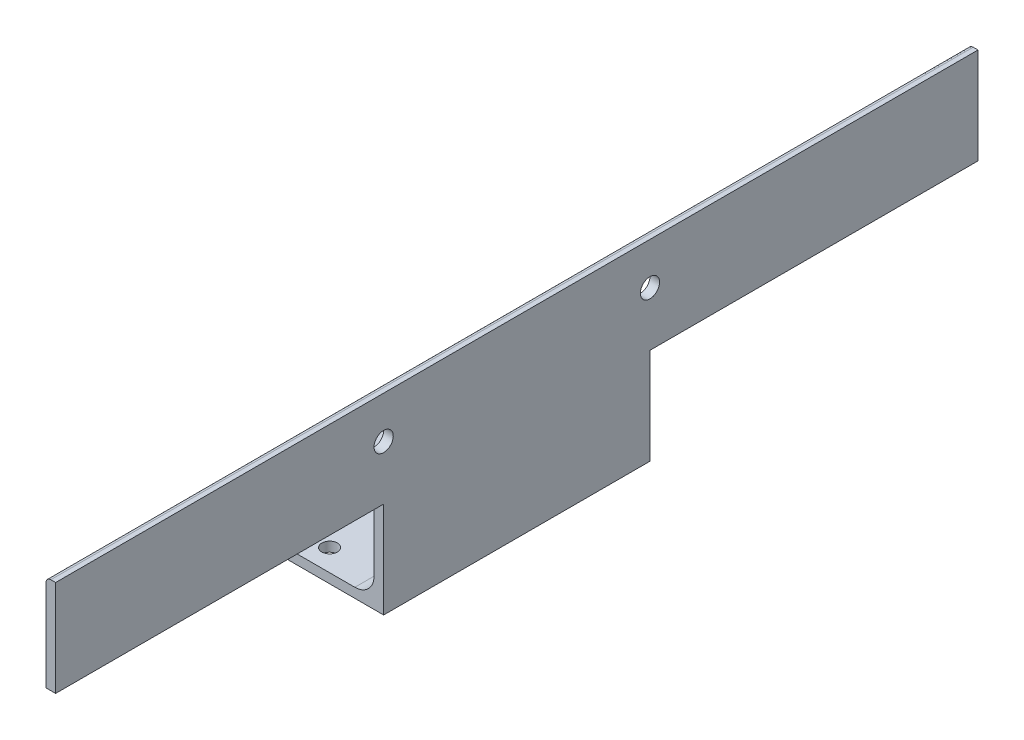
SolidWorks part; units mm, degrees
ref_plane "Front Plane" through (0, 0, 0) normal (0, 0, 1) x (1, 0, 0)
ref_plane "Top Plane" through (0, 0, 0) normal (0, 1, 0) x (1, 0, 0)
ref_plane "Right Plane" through (0, 0, 0) normal (1, 0, 0) x (0, 0, -1)
sketch "Sketch0" plane through (0, 0, 0) normal (0, 0, 1) x (1, 0, 0)
  line L0 (-31.75, -31.75) -> (31.75, -31.75)
  line L1 (31.75, -31.75) -> (31.75, 31.75)
  line L2 (31.75, 0) -> (0, 0) construction
  line L3 (0, 0) -> (0, -31.75) construction
  line L4 (28.575, -22.225) -> (28.575, 31.75) construction
  line L5 (22.225, -28.575) -> (-31.75, -28.575) construction
  arc A0 (28.575, -22.225) -> (22.225, -28.575) centre (22.225, -22.225) cw
  point P3 (26.7151, -26.7151)
  dimension "Inside Corner Radius" = 6.35
  dimension "Outside Height" = 63.5
  dimension "Inside Height" = 60.325
  dimension "Inside Width" = 60.325
  dimension "Wall Thickness" = 3.175
  dimension "D1" = 3.175
  dimension "Outside Width" = 63.5
sketch "Sketch1" plane through (0, 0, 0) normal (1, 0, 0) x (0, 0, -1)
  line L0 (152.4, 0) -> (-152.4, 0)
  point P4 (0, 0)
  dimension "Length" = 304.8
sketch "Sketch2" plane through (0, 0, 0) normal (0, 0, 1) x (1, 0, 0)
  line L0 (-31.75, -31.75) -> (31.75, -31.75)
  line L1 (31.75, -31.75) -> (31.75, 31.75)
  line L2 (31.75, 31.75) -> (28.575, 31.75) construction
  line L3 (28.575, 30.1625) -> (28.575, -22.225)
  line L4 (22.225, -28.575) -> (-30.1625, -28.575)
  line L5 (-31.75, -31.75) -> (-31.75, -28.575) construction
  line L6 (30.1625, 31.75) -> (31.75, 31.75)
  line L7 (-31.75, -30.1625) -> (-31.75, -31.75)
  line L8 (31.75, 0) -> (0, 0) construction
  line L9 (0, 0) -> (0, -31.75) construction
  arc A0 (28.575, 30.1625) -> (30.1625, 31.75) centre (30.1625, 30.1625) cw
  arc A1 (-31.75, -30.1625) -> (-30.1625, -28.575) centre (-30.1625, -30.1625) cw
  arc A2 (28.575, -22.225) -> (22.225, -28.575) centre (22.225, -22.225) cw
  dimension "Inside Radius" = 6.35
  dimension "Height" = 63.5
  dimension "Width" = 63.5
  dimension "Thickness" = 3.175
extrude "Boss-Extrude1" add sketch "Sketch2" along normal mid plane 304.8
sketch "Break Locations" plane through (0, 0, 0) normal (1, 0, 0) x (0, 0, -1)
  line L0 (-87.63, 0) -> (87.63, 0)
  line L1 (-152.4, -31.75) -> (-152.4, 31.75) construction
  line L2 (152.4, -31.75) -> (152.4, 31.75) construction
  point P0 (-98.425, 0)
  point P1 (98.425, 0)
  point P10 (0, 0)
  point P11 (87.63, 0)
  point P13 (-87.63, 0)
  dimension "D1" = 53.975
  dimension "D2" = 53.975
  dimension "D3" = 64.77
sketch "Sketch3" plane through (0, -28.575, 0) normal (0, 1, 0) x (1, 0, 0)
  line L0 (-3.9687, 152.4) -> (-3.9687, -152.4) construction
  line L1 (22.225, 152.4) -> (-30.1625, 152.4) construction
  line L2 (22.225, -152.4) -> (-30.1625, -152.4) construction
  line L3 (-27.3219, 0) -> (19.3844, 0) construction
  circle A0 centre (-14.3219, 8.79) radius 2.585
  circle A1 centre (6.6781, 8.79) radius 2.585
  circle A2 centre (-14.3219, 36.79) radius 2.585
  circle A3 centre (6.6781, 36.79) radius 2.585
  circle A4 centre (-14.3219, -36.79) radius 2.585
  circle A5 centre (6.6781, -36.79) radius 2.585
  circle A6 centre (6.6781, -8.79) radius 2.585
  circle A7 centre (-14.3219, -8.79) radius 2.585
  point P24 (-3.9688, 0)
  point P25 (-3.9687, 0)
  dimension "D1" = 5.17
  dimension "D2" = 5.17
  dimension "D3" = 28
  dimension "D4" = 8.79
  dimension "D5" = 8.79
  dimension "D6" = 28
extrude "Cut-Extrude1" cut sketch "Sketch3" against normal through all
sketch "Sketch4" plane through (31.75, 0, 0) normal (1, 0, 0) x (0, 0, -1)
  line L6 (-152.4, 0) -> (-44, 0)
  line L7 (-152.4, -31.75) -> (-152.4, 31.75) construction
  line L8 (-44, 0) -> (-44, -48.0447)
  line L9 (-44, -48.0447) -> (-168.6254, -48.0447)
  line L10 (-168.6254, -48.0447) -> (-168.6254, 0)
  line L11 (-168.6254, 0) -> (-152.4, 0)
  line L12 (0, 0) -> (0, -31.75) construction
  line L13 (-152.4, -31.75) -> (152.4, -31.75) construction
  line L14 (168.6254, -48.0447) -> (168.6254, 0)
  line L15 (44, -48.0447) -> (168.6254, -48.0447)
  line L16 (44, 0) -> (44, -48.0447)
  line L17 (152.4, 0) -> (44, 0)
  line L18 (168.6254, 0) -> (152.4, 0)
  dimension "D1" = 88
extrude "Cut-Extrude2" cut sketch "Sketch4" against normal through all
sketch "Sketch5" plane through (31.75, 0, 0) normal (1, 0, 0) x (0, 0, -1)
  line L0 (-44, 0) -> (44, 0) construction
  line L1 (44, 0) -> (44, -31.75) construction
  line L2 (0, -31.75) -> (0, 31.75) construction
  line L3 (-44, -31.75) -> (44, -31.75) construction
  line L4 (-152.4, 31.75) -> (152.4, 31.75) construction
  circle A0 centre (-44, 17.9042) radius 3.175
  circle A1 centre (44, 17.9042) radius 3.175
  dimension "D1" = 6.35
extrude "Cut-Extrude3" cut sketch "Sketch5" against normal through all
equation "\"D1@Break Locations\" = .85 * \"Height@Sketch2\""
equation "\"D2@Break Locations\"=\"D1@Break Locations\""
equation "\"Thickness@Sketch2\" = \"Wall Thickness@Sketch0\""
equation "\"Height@Sketch2\" = \"Outside Height@Sketch0\""
equation "\"Width@Sketch2\" = \"Outside Width@Sketch0\""
equation "\"Inside Radius@Sketch2\" = \"Inside Corner Radius@Sketch0\""
equation "\"Length@Boss-Extrude1\" = \"Length@Sketch1\""
equation "\"D3@Break Locations\"=\"D2@Break Locations\"*1.2"
equation "\"D1@Sketch0\"=\"Wall Thickness@Sketch0\""
